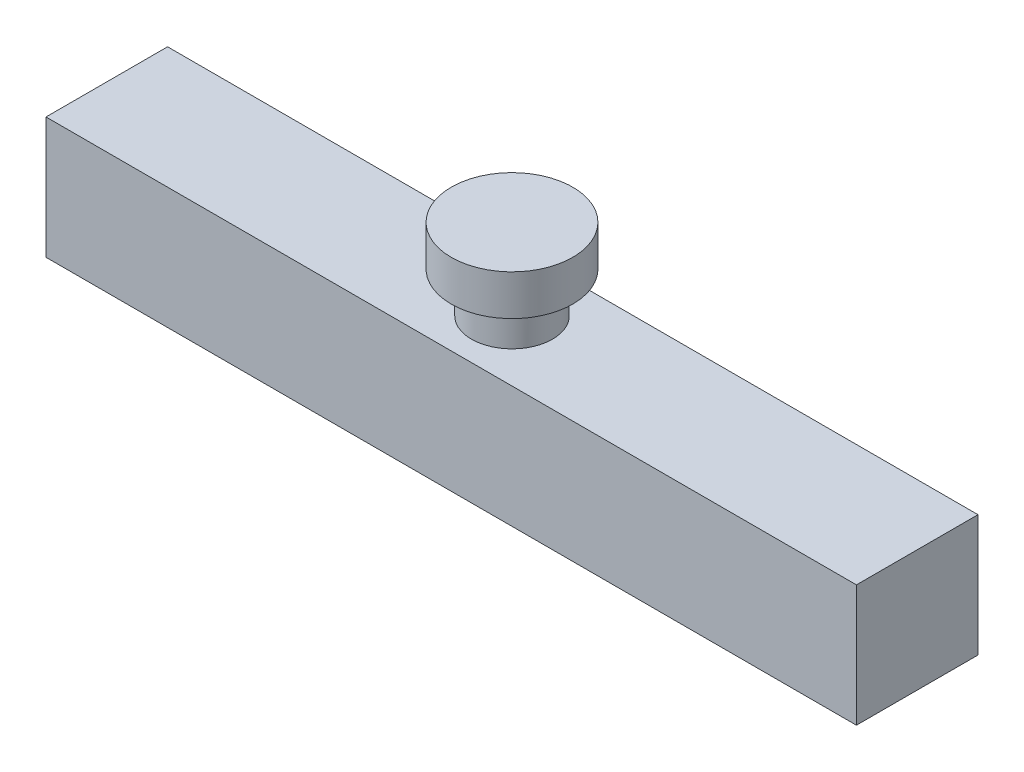
SolidWorks part; units mm, degrees
ref_plane "Front Plane" through (0, 0, 0) normal (0, 0, 1) x (1, 0, 0)
ref_plane "Top Plane" through (0, 0, 0) normal (0, 1, 0) x (1, 0, 0)
ref_plane "Right Plane" through (0, 0, 0) normal (1, 0, 0) x (0, 0, -1)
sketch "Sketch1" plane through (0, 0, 0) normal (0, 1, 0) x (1, 0, 0)
  line L0 (0, 0) -> (200, 0)
  line L1 (200, 0) -> (200, -60)
  line L2 (200, -60) -> (0, -60)
  line L3 (0, 0) -> (0, -60)
extrude "Boss-Extrude1" add sketch "Sketch1" against normal blind 30
sketch "Sketch2" plane through (0, 0, 0) normal (0, 1, 0) x (1, 0, 0)
  line L0 (0, -30) -> (100, -30)
  line L1 (0, 0) -> (0, -60) construction
  circle A0 centre (100, -30) radius 10
extrude "Boss-Extrude3" add sketch "Sketch2" along normal blind 10
sketch "Sketch3" plane through (0, 10, 0) normal (0, 1, 0) x (1, 0, 0)
  circle A0 centre (100, -30) radius 15
extrude "Boss-Extrude4" add sketch "Sketch3" along normal blind 10
sketch "Sketch4" plane through (0, 0, 0) normal (0, 1, 0) x (1, 0, 0)
  line L0 (0, 0) -> (0, -15)
  line L2 (0, 0) -> (0, -60) construction
  line L3 (0, -15) -> (200, -15)
  line L4 (200, -60) -> (200, 0) construction
  line L5 (200, -15) -> (200, 0)
  line L6 (200, 0) -> (0, 0)
  line L7 (0, -60) -> (0, -45)
  line L8 (0, -45) -> (200, -45)
  line L9 (200, -45) -> (200, -60)
  line L10 (200, -60) -> (0, -60)
extrude "Cut-Extrude1" cut sketch "Sketch4" against normal blind 50
